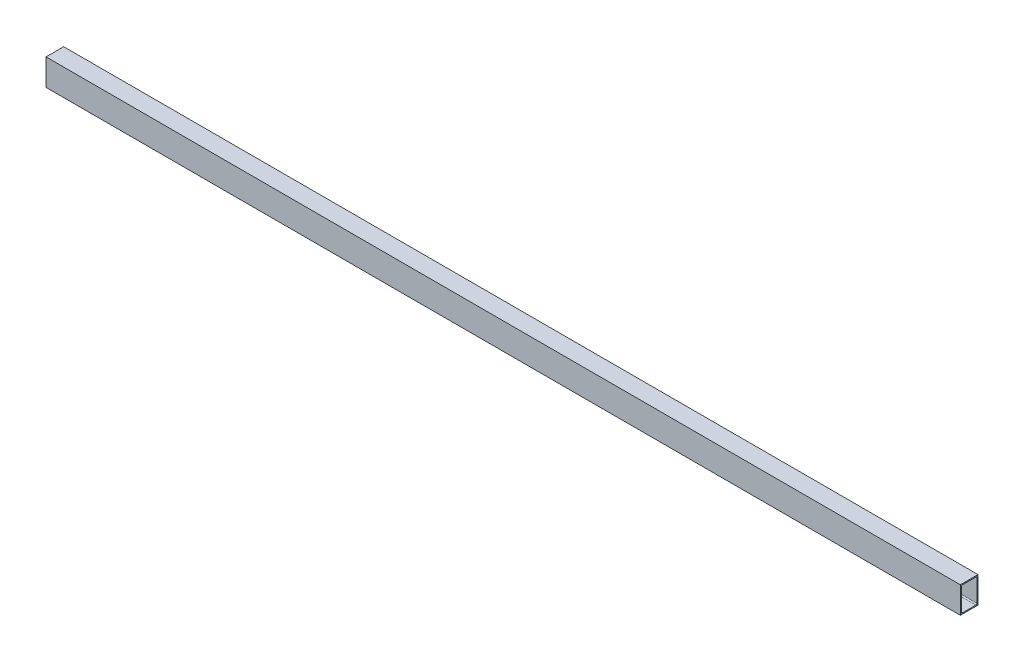
SolidWorks part; units mm, degrees
material "ASTM A500 Grade B Steel"
ref_plane "Front Plane" through (0, 0, 0) normal (0, 0, 1) x (1, 0, 0)
ref_plane "Top Plane" through (0, 0, 0) normal (0, 1, 0) x (1, 0, 0)
ref_plane "Right Plane" through (0, 0, 0) normal (1, 0, 0) x (0, 0, -1)
sketch "Sketch1" plane through (0, 0, 0) normal (1, 0, 0) x (0, 0, -1)
  line L0 (-95.25, 12.7) -> (-95.25, 139.7)
  line L1 (0, 0) -> (-101.6, 0)
  line L2 (0, 0) -> (0, 152.4)
  line L3 (0, 152.4) -> (-101.6, 152.4)
  line L4 (-101.6, 0) -> (-101.6, 152.4)
  line L5 (-12.7, 146.05) -> (-88.9, 146.05)
  line L6 (-6.35, 12.7) -> (-6.35, 139.7)
  line L7 (-12.7, 6.35) -> (-88.9, 6.35)
  line L8 (-95.25, 6.35) -> (-95.25, 146.05) construction
  line L9 (-6.35, 6.35) -> (-95.25, 6.35) construction
  line L10 (-6.35, 6.35) -> (-6.35, 146.05) construction
  line L11 (-6.35, 146.05) -> (-95.25, 146.05) construction
  arc A0 (-95.25, 12.7) -> (-88.9, 6.35) centre (-88.9, 12.7) ccw
  arc A1 (-6.35, 12.7) -> (-12.7, 6.35) centre (-12.7, 12.7) cw
  arc A2 (-12.7, 146.05) -> (-6.35, 139.7) centre (-12.7, 139.7) cw
  arc A3 (-95.25, 139.7) -> (-88.9, 146.05) centre (-88.9, 139.7) cw
  dimension "D4" = 6.35
  dimension "D1" = 152.4
  dimension "D2" = 101.6
  dimension "D3" = 6.35
extrude "Boss-Extrude1" add sketch "Sketch1" along normal blind 5265.2
equation "\"D4@Sketch1\"= \"D3@Sketch1\""
